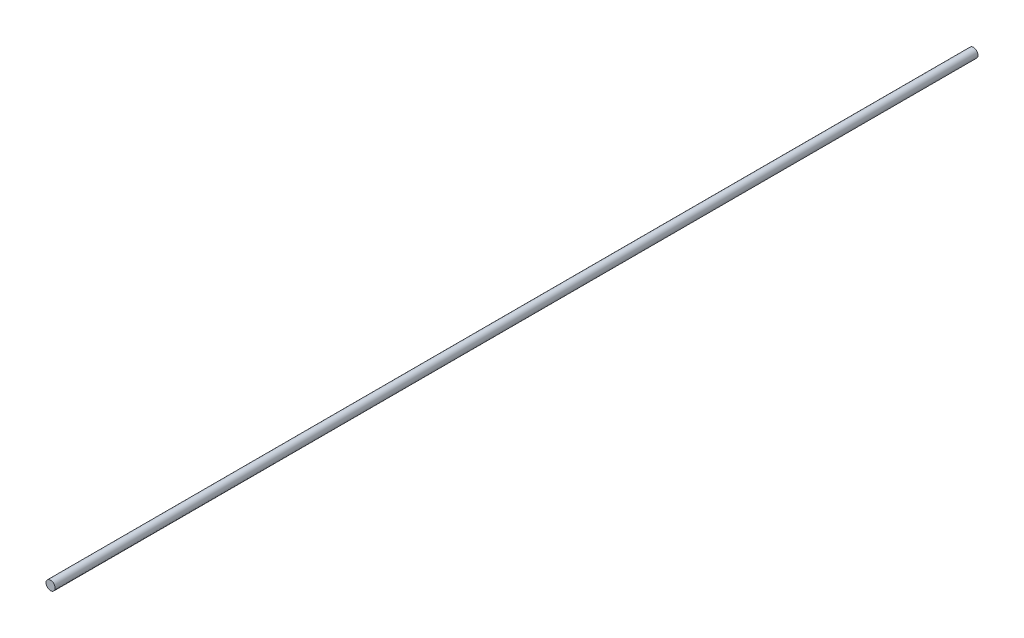
SolidWorks part; units mm, degrees
material "Plain Carbon Steel"
ref_plane "Front Plane" through (0, 0, 0) normal (0, 0, 1) x (1, 0, 0)
ref_plane "Top Plane" through (0, 0, 0) normal (0, 1, 0) x (1, 0, 0)
ref_plane "Right Plane" through (0, 0, 0) normal (1, 0, 0) x (0, 0, -1)
sketch "Sketch1" plane through (0, 0, 0) normal (0, 0, 1) x (1, 0, 0)
  circle A0 centre (0, 0) radius 4
  dimension "D1" = 8
extrude "Boss-Extrude1" add sketch "Sketch1" along normal blind 810
